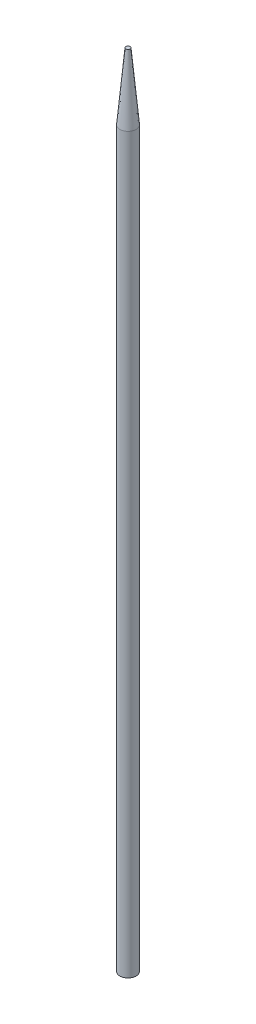
SolidWorks part; units mm, degrees
ref_plane "Front Plane" through (0, 0, 0) normal (0, 0, 1) x (1, 0, 0)
ref_plane "Top Plane" through (0, 0, 0) normal (0, 1, 0) x (1, 0, 0)
ref_plane "Right Plane" through (0, 0, 0) normal (1, 0, 0) x (0, 0, -1)
sketch "Sketch1" plane through (0, 0, 0) normal (1, 0, 0) x (0, 0, -1)
  line L0 (0, 0) -> (0, 152.4)
  line L2 (1.5494, 139.7) -> (1.5494, 0)
  line L3 (1.5494, 0) -> (0, 0)
  line L4 (0, 152.4) -> (0.4064, 152.4)
  line L5 (0.4064, 152.4) -> (1.5494, 139.7)
  dimension "D1" = 0.4064
  dimension "D2" = 1.5494
  dimension "D3" = 12.7
  dimension "D4" = 152.4
revolve "Revolve1" add sketch "Sketch1" angle 360 about L0
